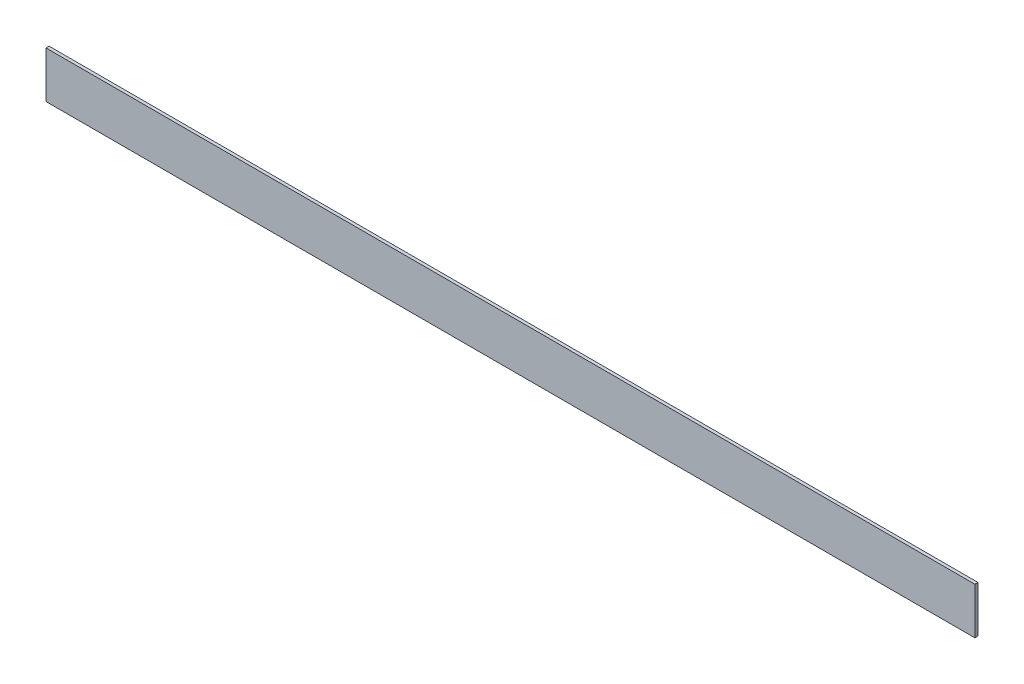
SolidWorks part; units mm, degrees
ref_plane "Plan de face" through (0, 0, 0) normal (0, 0, 1) x (1, 0, 0)
ref_plane "Plan de dessus" through (0, 0, 0) normal (0, 1, 0) x (1, 0, 0)
ref_plane "Plan de droite" through (0, 0, 0) normal (1, 0, 0) x (0, 0, -1)
sketch "Esquisse1" plane through (0, 0, 0) normal (0, 0, 1) x (1, 0, 0)
  line L1 (0, 0) -> (600, 0)
  line L2 (0, 0) -> (0, 30)
  line L3 (0, 30) -> (600, 30)
  line L4 (600, 0) -> (600, 30)
  dimension "D1" = 600
  dimension "D2" = 30
extrude "Boss.-Extru.1" add sketch "Esquisse1" along normal blind 2
